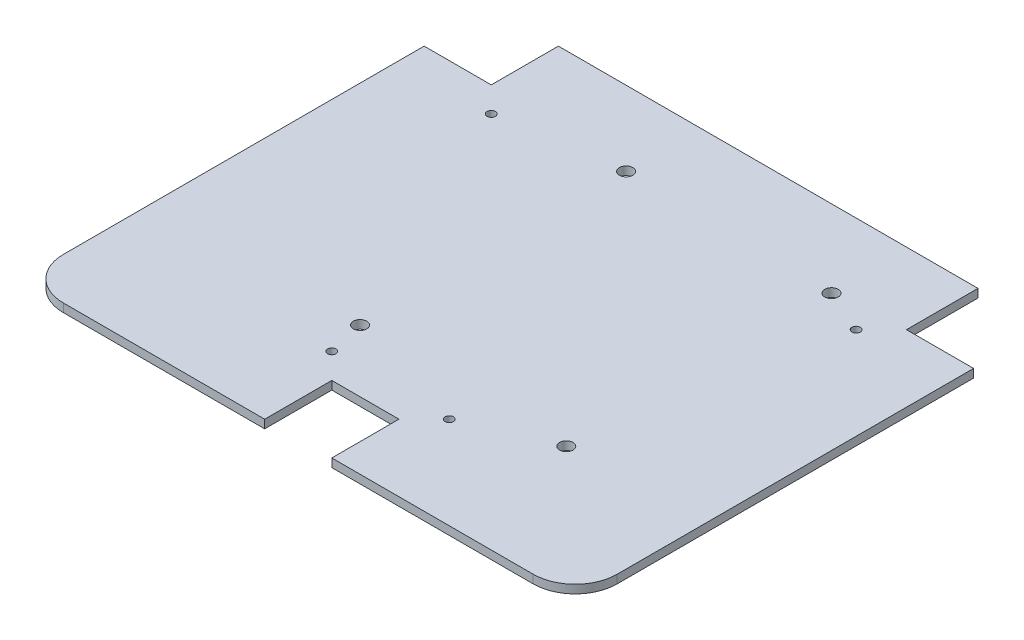
SolidWorks part; units mm, degrees
ref_plane "Plano frontal" through (0, 0, 0) normal (0, 0, 1) x (1, 0, 0)
ref_plane "Plano superior" through (0, 0, 0) normal (0, 1, 0) x (1, 0, 0)
ref_plane "Plano direito" through (0, 0, 0) normal (1, 0, 0) x (0, 0, -1)
sketch "Esboço1" plane through (0, 0, 0) normal (0, 1, 0) x (1, 0, 0)
  line L0 (504.2674, -155.797) -> (384.2674, -155.797)
  line L1 (359.2674, -130.797) -> (359.2674, 84.203)
  line L2 (399.2674, 124.203) -> (649.2674, 124.203)
  line L3 (689.2674, -155.797) -> (399.2674, 84.203) construction
  line L4 (359.2674, -155.797) -> (649.2674, 81.5882) construction
  line L5 (649.2674, 124.203) -> (649.2674, 81.5882)
  line L6 (649.2674, 81.5882) -> (689.2674, 81.5882)
  line L7 (689.2674, 81.5882) -> (689.2674, -130.797)
  line L8 (664.2674, -155.797) -> (544.2674, -155.797)
  line L9 (544.2674, -115.797) -> (689.2674, -115.797) construction
  line L10 (504.2674, -115.797) -> (359.2674, -115.797) construction
  line L11 (504.2674, -115.797) -> (504.2674, 124.203) construction
  line L14 (399.2674, 124.203) -> (399.2674, 84.203)
  line L15 (399.2674, 84.203) -> (359.2674, 84.203)
  line L17 (504.2674, -100.797) -> (504.2674, -115.797) construction
  line L22 (544.2674, -155.797) -> (544.2674, -115.797)
  line L23 (544.2674, -115.797) -> (504.2674, -115.797)
  line L24 (504.2674, -115.797) -> (504.2674, -155.797)
  arc A0 (359.2674, -130.797) -> (384.2674, -155.797) centre (384.2674, -130.797) ccw
  arc A1 (664.2674, -155.797) -> (689.2674, -130.797) centre (664.2674, -130.797) ccw
  dimension "D3" = 25
  dimension "D8" = 40
  dimension "D13" = 40
  dimension "D16" = 40
  dimension "D2" = 250
  dimension "D11" = 40
  dimension "D14" = 40
  dimension "D15" = 145
extrude "Ressalto-extrusão4" add sketch "Esboço1" along normal blind 5
sketch "Esboço2" plane through (0, 5, 0) normal (0, 1, 0) x (1, 0, 0)
  line L0 (649.2674, 81.5882) -> (649.2674, 66.5882) construction
  line L1 (399.2674, 84.203) -> (414.2674, 84.203) construction
  line L2 (414.2674, 84.203) -> (414.2674, 69.203) construction
  line L3 (414.2674, 69.203) -> (399.2674, 69.203) construction
  line L4 (399.2674, 69.203) -> (399.2674, 84.203) construction
  line L5 (544.2674, -115.797) -> (559.2674, -115.797) construction
  line L6 (559.2674, -115.797) -> (559.2674, -100.797) construction
  line L7 (559.2674, -100.797) -> (544.2674, -100.797) construction
  line L8 (544.2674, -100.797) -> (544.2674, -115.797) construction
  line L9 (504.2674, -115.797) -> (504.2674, -100.797) construction
  line L10 (504.2674, -100.797) -> (489.2674, -100.797) construction
  line L11 (489.2674, -100.797) -> (489.2674, -115.797) construction
  line L12 (489.2674, -115.797) -> (504.2674, -115.797) construction
  line L13 (649.2674, 66.5882) -> (634.2674, 66.5882) construction
  circle A0 centre (559.2674, -100.797) radius 2.5
  circle A1 centre (489.2674, -100.797) radius 2.5
  circle A2 centre (634.2674, 66.5882) radius 2.5
  circle A3 centre (414.2674, 69.203) radius 2.5
  dimension "D1" = 15
  dimension "D6" = 15
  dimension "D2" = 15
  dimension "D3" = 15
  dimension "D4" = 15
  dimension "D5" = 15
  dimension "D7" = 15
  dimension "D8" = 15
extrude "Corte-extrusão1" cut sketch "Esboço2" against normal blind 5
sketch "Esboço3" plane through (0, 5, 0) normal (0, 1, 0) x (1, 0, 0)
  line L0 (489.2674, -98.297) -> (489.2674, -78.797) construction
  line L1 (489.2674, -78.797) -> (484.0818, -78.797) construction
  line L2 (484.0818, -78.797) -> (608.0818, -79.9132) construction
  line L3 (484.0818, -78.797) -> (484.0818, 79.7119) construction
  line L4 (484.0818, 79.7119) -> (608.0818, 78.0868) construction
  line L5 (544.2674, -115.797) -> (504.2674, -115.797) construction
  line L6 (608.0818, -79.9132) -> (608.0818, 78.0868) construction
  circle A0 centre (489.2674, -100.797) radius 2.5 construction
  circle A1 centre (604.5818, -79.9132) radius 3.5 construction
  circle A2 centre (608.0818, -79.9132) radius 4
  circle A3 centre (484.0818, -78.797) radius 4
  circle A4 centre (604.5818, 78.0868) radius 3.5 construction
  circle A5 centre (484.0818, 79.7119) radius 4
  circle A6 centre (608.0818, 78.0868) radius 4
  dimension "D1" = 124
  dimension "D2" = 37
extrude "Corte-extrusão2" cut sketch "Esboço3" against normal blind 5
